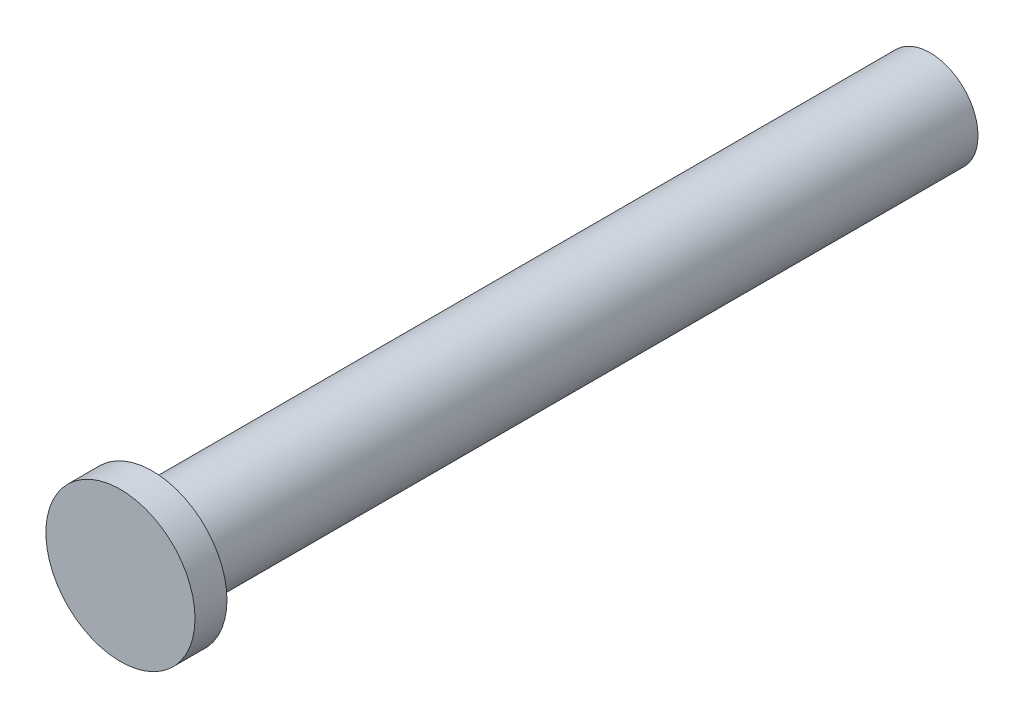
SolidWorks part; units mm, degrees
ref_plane "Front Plane" through (0, 0, 0) normal (1, 0, 0) x (0, 1, 0)
ref_plane "Top Plane" through (0, 0, 0) normal (0, 0, 1) x (0, 1, 0)
ref_plane "Right Plane" through (0, 0, 0) normal (0, 1, 0) x (-1, 0, 0)
sketch "Sketch1" plane through (0, 0, 0) normal (1, 0, 0) x (0, 1, 0)
  line L0 (0, 219.1333) -> (0, -279.3) construction
  line L1 (0, 219.1333) -> (35, 219.1333)
  line L2 (35, 219.1333) -> (35, 204.1333)
  line L3 (35, 204.1333) -> (22.5, 204.1333)
  line L4 (22.5, 204.1333) -> (22.5, -160.8667)
  line L5 (22.5, -160.8667) -> (0, -160.8667)
  line L6 (0, 219.1333) -> (0, -160.8667)
  dimension "D1" = 380
  dimension "D2" = 35
  dimension "D3" = 22.5
  dimension "D4" = 15
revolve "Revolve1" add sketch "Sketch1" angle 360 about L0
